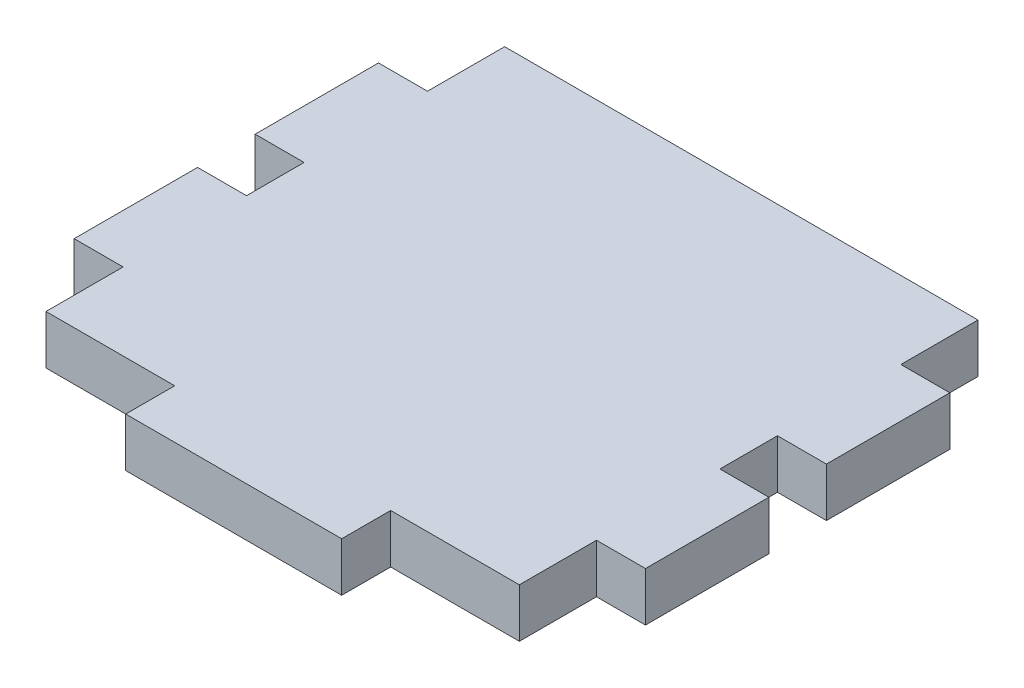
SolidWorks part; units mm, degrees
ref_plane "Front Plane" through (0, 0, 0) normal (0, 0, 1) x (1, 0, 0)
ref_plane "Top Plane" through (0, 0, 0) normal (0, 1, 0) x (1, 0, 0)
ref_plane "Right Plane" through (0, 0, 0) normal (1, 0, 0) x (0, 0, -1)
sketch "Sketch1" plane through (0, 0, 0) normal (0, 1, 0) x (1, 0, 0)
  line L1 (-15.3423, -14.865) -> (15.3423, -14.865)
  line L2 (-15.3423, -14.865) -> (-15.3423, 14.865)
  line L3 (-15.3423, 14.865) -> (15.3423, 14.865)
  line L4 (15.3423, -14.865) -> (15.3423, 14.865)
  line L5 (-15.3423, -14.865) -> (15.3423, 14.865) construction
  line L6 (-15.3423, 14.865) -> (15.3423, -14.865) construction
  line L7 (-15.3423, 9.865) -> (-18.5173, 9.865)
  line L8 (-15.3423, 9.865) -> (-15.3423, 1.865)
  line L9 (-15.3423, 1.865) -> (-18.5173, 1.865)
  line L10 (-18.5173, 9.865) -> (-18.5173, 1.865)
  line L11 (-15.3423, -1.865) -> (-18.5173, -1.865)
  line L12 (-15.3423, -1.865) -> (-15.3423, -9.865)
  line L13 (-15.3423, -9.865) -> (-18.5173, -9.865)
  line L14 (-18.5173, -1.865) -> (-18.5173, -9.865)
  line L15 (15.3423, 9.865) -> (18.5173, 9.865)
  line L16 (15.3423, 9.865) -> (15.3423, 1.865)
  line L17 (15.3423, 1.865) -> (18.5173, 1.865)
  line L18 (18.5173, 9.865) -> (18.5173, 1.865)
  line L19 (15.3423, -1.865) -> (18.5173, -1.865)
  line L20 (15.3423, -1.865) -> (15.3423, -9.865)
  line L21 (15.3423, -9.865) -> (18.5173, -9.865)
  line L22 (18.5173, -1.865) -> (18.5173, -9.865)
  point P0 (0, 0)
  dimension "D1" = 30.6846
  dimension "D2" = 3.175
  dimension "D3" = 3.175
  dimension "D4" = 3.175
  dimension "D5" = 3.175
  dimension "D6" = 29.73
  dimension "D7" = 5
  dimension "D8" = 5
  dimension "D9" = 8
  dimension "D10" = 8
  dimension "D11" = 5
  dimension "D12" = 8
  dimension "D13" = 8
  dimension "D14" = 5
extrude "Boss-Extrude1" add sketch "Sketch1" along normal blind 3.175 contours L7 L10 L9 L2 | L1 L4 L3 L2 | L22 L19 L4 L21 | L18 L15 L4 L17 | L11 L14 L13 L2
sketch "Sketch2" plane through (0, 0, 14.865) normal (0, 0, 1) x (1, 0, 0)
  line L1 (-15.3423, 3.175) -> (15.3423, 3.175)
  line L2 (-15.3423, 3.175) -> (-15.3423, 0)
  line L3 (-15.3423, 0) -> (15.3423, 0)
  line L4 (15.3423, 3.175) -> (15.3423, 0)
  line L5 (-7, 3.175) -> (7, 3.175)
  line L6 (-7, 3.175) -> (-7, 0)
  line L7 (-7, 0) -> (7, 0)
  line L8 (7, 3.175) -> (7, 0)
  dimension "D1" = 7
  dimension "D2" = 14
extrude "Boss-Extrude5" add sketch "Sketch2" along normal blind 3.175 contours L8 L1 L6 L3
